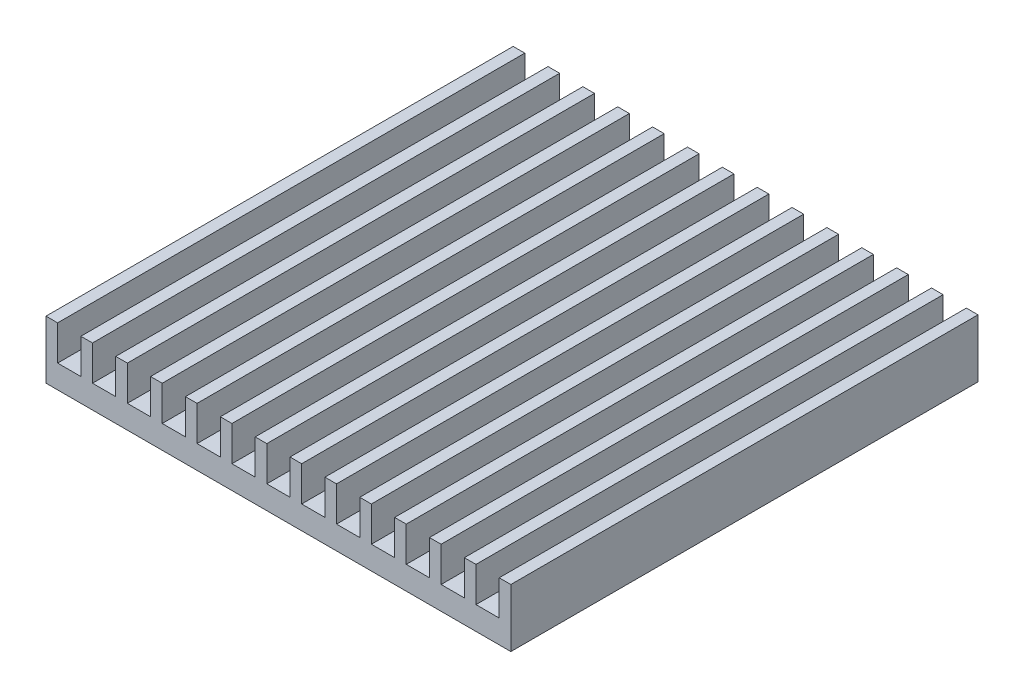
SolidWorks part; units mm, degrees
ref_plane "前视基准面" through (0, 0, 0) normal (0, 0, 1) x (1, 0, 0)
ref_plane "上视基准面" through (0, 0, 0) normal (0, 1, 0) x (1, 0, 0)
ref_plane "右视基准面" through (0, 0, 0) normal (1, 0, 0) x (0, 0, -1)
other "Configuration Table"
sketch "草图1" plane through (0, 0, 0) normal (0, 1, 0) x (1, 0, 0)
  line L1 (-20, 20.1) -> (20, 20.1)
  line L2 (-20, 20.1) -> (-20, -20.1)
  line L3 (-20, -20.1) -> (20, -20.1)
  line L4 (20, 20.1) -> (20, -20.1)
  line L5 (-20, 20.1) -> (20, -20.1) construction
  line L6 (-20, -20.1) -> (20, 20.1) construction
  point P0 (0, 0)
  dimension "D1" = 40.2
  dimension "D2" = 40
extrude "凸台-拉伸1" add sketch "草图1" along normal blind 2
sketch "草图2" plane through (0, 2, 0) normal (0, 1, 0) x (1, 0, 0)
  line L0 (-20, -20.1) -> (20, -20.1) construction
  line L1 (-20, 20.1) -> (-19, 20.1)
  line L2 (-20, 20.1) -> (-20, -20.1)
  line L3 (-20, -20.1) -> (-19, -20.1)
  line L4 (-19, 20.1) -> (-19, -20.1)
  line L5 (-17, 20.1) -> (-16, 20.1)
  line L6 (-17, 20.1) -> (-17, -20.1)
  line L7 (-17, -20.1) -> (-16, -20.1)
  line L8 (-16, 20.1) -> (-16, -20.1)
  line L9 (-14, 20.1) -> (-13, 20.1)
  line L10 (-14, 20.1) -> (-14, -20.1)
  line L11 (-14, -20.1) -> (-13, -20.1)
  line L12 (-13, 20.1) -> (-13, -20.1)
  line L13 (-11, 20.1) -> (-10, 20.1)
  line L14 (-11, 20.1) -> (-11, -20.1)
  line L15 (-11, -20.1) -> (-10, -20.1)
  line L16 (-10, 20.1) -> (-10, -20.1)
  line L17 (-8, 20.1) -> (-7, 20.1)
  line L18 (-8, 20.1) -> (-8, -20.1)
  line L19 (-8, -20.1) -> (-7, -20.1)
  line L20 (-7, 20.1) -> (-7, -20.1)
  line L21 (-5, 20.1) -> (-4, 20.1)
  line L22 (-5, 20.1) -> (-5, -20.1)
  line L23 (-5, -20.1) -> (-4, -20.1)
  line L24 (-4, 20.1) -> (-4, -20.1)
  line L25 (-2, 20.1) -> (-1, 20.1)
  line L26 (-2, 20.1) -> (-2, -20.1)
  line L27 (-2, -20.1) -> (-1, -20.1)
  line L28 (-1, 20.1) -> (-1, -20.1)
  line L29 (1, 20.1) -> (2, 20.1)
  line L30 (1, 20.1) -> (1, -20.1)
  line L31 (1, -20.1) -> (2, -20.1)
  line L32 (2, 20.1) -> (2, -20.1)
  line L33 (4, 20.1) -> (5, 20.1)
  line L34 (4, 20.1) -> (4, -20.1)
  line L35 (4, -20.1) -> (5, -20.1)
  line L36 (5, 20.1) -> (5, -20.1)
  line L37 (7, 20.1) -> (8, 20.1)
  line L38 (7, 20.1) -> (7, -20.1)
  line L39 (7, -20.1) -> (8, -20.1)
  line L40 (8, 20.1) -> (8, -20.1)
  line L41 (10, 20.1) -> (11, 20.1)
  line L42 (10, 20.1) -> (10, -20.1)
  line L43 (10, -20.1) -> (11, -20.1)
  line L44 (11, 20.1) -> (11, -20.1)
  line L45 (13, 20.1) -> (14, 20.1)
  line L46 (13, 20.1) -> (13, -20.1)
  line L47 (13, -20.1) -> (14, -20.1)
  line L48 (14, 20.1) -> (14, -20.1)
  line L49 (16, 20.1) -> (17, 20.1)
  line L50 (16, 20.1) -> (16, -20.1)
  line L51 (16, -20.1) -> (17, -20.1)
  line L52 (17, 20.1) -> (17, -20.1)
  line L53 (19, 20.1) -> (20, 20.1)
  line L54 (19, 20.1) -> (19, -20.1)
  line L55 (19, -20.1) -> (20, -20.1)
  line L56 (20, 20.1) -> (20, -20.1)
  dimension "D1" = 1
  dimension "D2" = 14
extrude "凸台-拉伸2" add sketch "草图2" along normal blind 3
